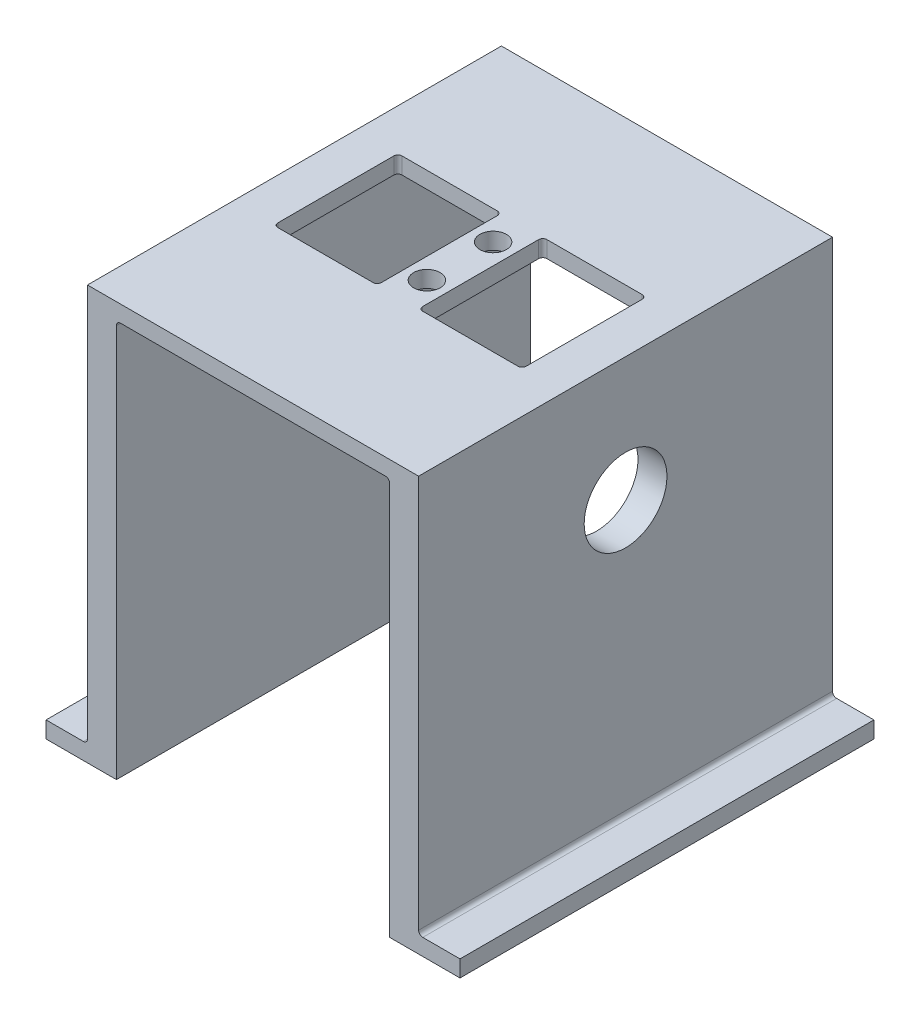
SolidWorks part; units mm, degrees
ref_plane "前视基准面" through (0, 0, 0) normal (0, 0, 1) x (1, 0, 0)
ref_plane "上视基准面" through (0, 0, 0) normal (0, 1, 0) x (1, 0, 0)
ref_plane "右视基准面" through (0, 0, 0) normal (1, 0, 0) x (0, 0, -1)
sketch "草图1" plane through (0, 0, 0) normal (0, 0, 1) x (1, 0, 0)
  line L0 (0, 0) -> (-25, 0)
  line L1 (-25, 0) -> (-25, 50)
  line L2 (-25, 50) -> (25, 50)
  line L3 (25, 50) -> (25, 0)
  line L4 (25, 0) -> (0, 0)
extrude "凸台-拉伸1" add sketch "草图1" along normal mid plane 50
sketch "草图2" plane through (0, 0, 0) normal (0, 0, 1) x (1, 0, 0)
  line L0 (-25, 50) -> (-20, 50)
  line L1 (25, 50) -> (-25, 50) construction
  line L2 (-20, 50) -> (-20, 2.5)
  line L3 (-20.5, 2) -> (-25, 2)
  line L4 (-25, 50) -> (-25, 0) construction
  line L5 (-25, 2) -> (-25, 50)
  line L6 (25, 50) -> (20, 50)
  line L7 (20, 50) -> (20, 2.5)
  line L8 (20.5, 2) -> (25, 2)
  line L9 (25, 0) -> (25, 50) construction
  line L10 (25, 2) -> (25, 50)
  line L11 (-16.5, 0) -> (16.5, 0)
  line L13 (-16, 48) -> (16, 48)
  line L14 (16.5, 47.5) -> (16.5, 0)
  line L16 (-25, 0) -> (25, 0) construction
  line L18 (-16.5, 0) -> (-16.5, 47.5)
  arc A0 (20.5, 2) -> (20, 2.5) centre (20.5, 2.5) cw
  arc A1 (-20.5, 2) -> (-20, 2.5) centre (-20.5, 2.5) ccw
  arc A2 (16, 48) -> (16.5, 47.5) centre (16, 47.5) cw
  arc A3 (-16.5, 47.5) -> (-16, 48) centre (-16, 47.5) cw
  dimension "D1" = 0.5
  dimension "D2" = 0.5
extrude "切除-拉伸1" cut sketch "草图2" against normal mid plane 50
ref_plane "基准面1" through (0, 50, 0) normal (0, 1, 0) x (1, 0, 0)
sketch "草图3" plane through (0, 50, 0) normal (0, 1, 0) x (1, 0, 0)
  line L0 (3, 7.5) -> (14.5, 7.5)
  line L1 (14.5, -7.5) -> (3, -7.5)
  line L2 (-14.5, 7.5) -> (-3, 7.5)
  line L3 (15, 7) -> (15, -7)
  line L4 (-15, -7) -> (-15, 7)
  line L5 (-3, -7.5) -> (-14.5, -7.5)
  line L6 (-2.5, 0) -> (-2.5, 7)
  line L7 (-2.5, 0) -> (-2.5, -7)
  line L8 (2.5, 7) -> (2.5, -7)
  arc A0 (14.5, 7.5) -> (15, 7) centre (14.5, 7) cw
  arc A1 (15, -7) -> (14.5, -7.5) centre (14.5, -7) cw
  arc A2 (-14.5, -7.5) -> (-15, -7) centre (-14.5, -7) cw
  arc A3 (-15, 7) -> (-14.5, 7.5) centre (-14.5, 7) cw
  arc A4 (3, 7.5) -> (2.5, 7) centre (3, 7) ccw
  arc A5 (3, -7.5) -> (2.5, -7) centre (3, -7) cw
  arc A6 (-3, -7.5) -> (-2.5, -7) centre (-3, -7) ccw
  arc A7 (-2.5, 7) -> (-3, 7.5) centre (-3, 7) ccw
  circle A8 centre (0, 4) radius 1.6
  circle A9 centre (0, -4) radius 1.6
  point P21 (2.5, 7.5)
  point P26 (-2.5, -7.5)
  dimension "D1" = 0.5
  dimension "D2" = 0.5
extrude "切除-拉伸2" cut sketch "草图3" against normal blind 2
sketch "草图4" plane through (0, 0, 0) normal (1, 0, 0) x (0, 0, -1)
  circle A1 centre (0, 35) radius 5
extrude "切除-拉伸3" cut sketch "草图4" against normal mid plane 50
